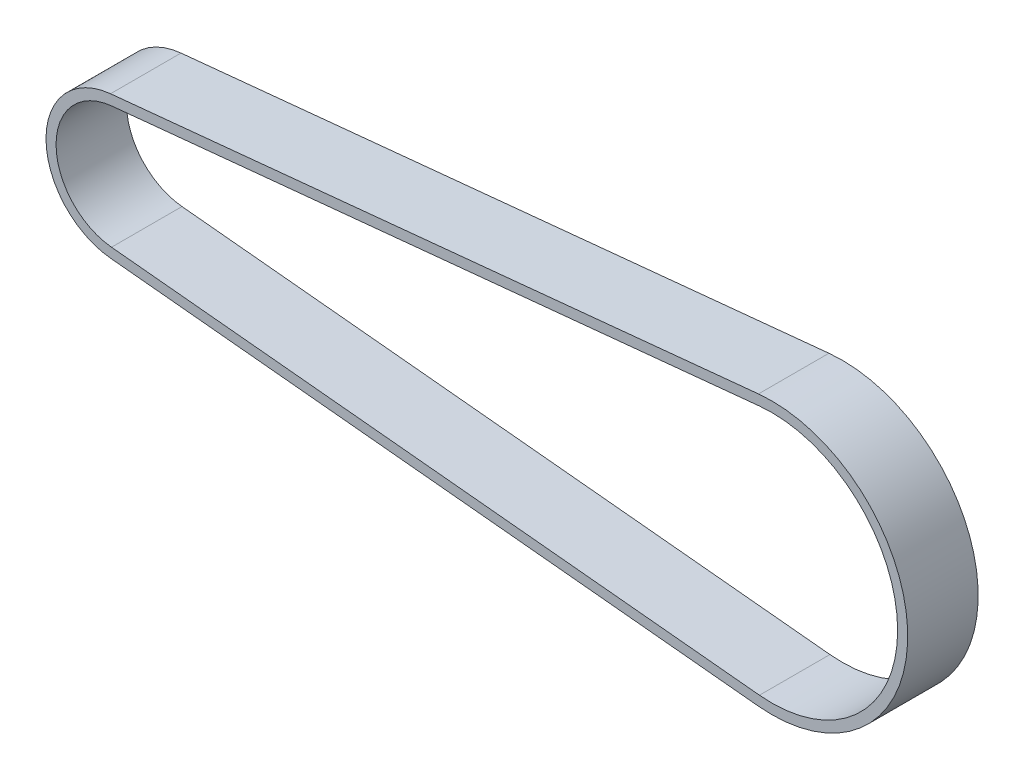
SolidWorks part; units mm, degrees
ref_plane "Front Plane" through (0, 0, 0) normal (0, 0, 1) x (1, 0, 0)
ref_plane "Top Plane" through (0, 0, 0) normal (0, 1, 0) x (1, 0, 0)
ref_plane "Right Plane" through (0, 0, 0) normal (1, 0, 0) x (0, 0, -1)
sketch "Sketch1" plane through (0, 0, 0) normal (0, 0, 1) x (1, 0, 0)
  line L0 (-0.6007, 6.0804) -> (63.7712, 12.4395)
  line L1 (0, 0) -> (54.5, 0) construction
  line L2 (-0.6007, -6.0804) -> (63.7712, -12.4395)
  line L3 (-0.699, 7.0756) -> (63.6728, 13.4346)
  line L4 (-0.699, -7.0756) -> (63.6728, -13.4346)
  arc A0 (-0.6007, 6.0804) -> (-0.6007, -6.0804) centre (0, 0) ccw
  arc A1 (63.7712, -12.4395) -> (63.7712, 12.4395) centre (65, 0) ccw
  arc A2 (63.6728, -13.4346) -> (63.6728, 13.4346) centre (65, 0) ccw
  arc A3 (-0.699, 7.0756) -> (-0.699, -7.0756) centre (0, 0) ccw
  dimension "D1" = 25
  dimension "D2" = 12.22
  dimension "D3" = 65
  dimension "D4" = 1
extrude "Boss-Extrude1" add sketch "Sketch1" along normal blind 7
